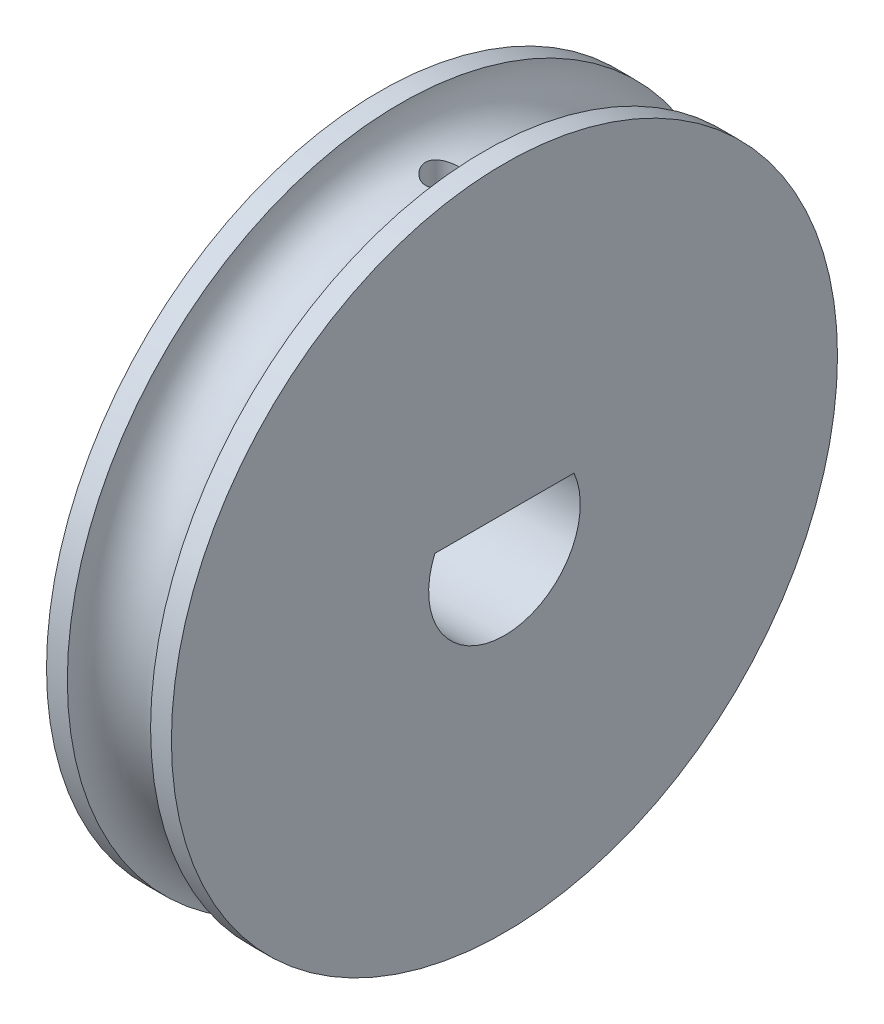
SolidWorks part; units mm, degrees
ref_plane "Front Plane" through (0, 0, 0) normal (0, 0, 1) x (1, 0, 0)
ref_plane "Top Plane" through (0, 0, 0) normal (0, 1, 0) x (1, 0, 0)
ref_plane "Right Plane" through (0, 0, 0) normal (1, 0, 0) x (0, 0, -1)
sketch "Sketch1" plane through (0, 0, 0) normal (1, 0, 0) x (0, 0, -1)
  line L0 (0, 0) -> (0, 9.1978)
  line L1 (-21.2164, 9.1978) -> (21.2164, 9.1978)
  circle A0 centre (0, 0) radius 101.6
  circle A1 centre (0, 0) radius 23.1244
  point P7 (0, 9.1978)
  point P8 (0, 0)
  dimension "D1" = 203.2
  dimension "D3" = 46.2487
  dimension "D2" = 9.1978
extrude "Boss-Extrude1" add sketch "Sketch1" against normal blind 38.1 contours A0 A1 | L1 A1
ref_plane "Plane1" through (0, 101.6, 0) normal (0, 1, 0) x (1, 0, 0)
sketch "Sketch2" plane through (0, 101.6, 0) normal (0, 1, 0) x (1, 0, 0)
  line L0 (-19.05, 101.6) -> (-19.05, -101.6) construction
  line L1 (0, 101.6) -> (-38.1, 101.6) construction
  line L2 (-38.1, -101.6) -> (0, -101.6) construction
  circle A0 centre (-19.05, 0) radius 5
  dimension "D1" = 10
extrude "Cut-Extrude1" cut sketch "Sketch2" against normal blind 63.5 contours L0 A0 | A0 L0
sketch "Sketch3" plane through (0, 38.1, 0) normal (0, 1, 0) x (1, 0, 0)
  circle A0 centre (-19.05, 0) radius 5 construction
  circle A1 centre (-19.05, 0) radius 5
  circle A2 centre (-19.05, 0) radius 1.5
  dimension "D1" = 3
extrude "Cut-Extrude4" cut sketch "Sketch3" against normal up to surface (28.9022 mm away) contours A2 up to face at (-19.05, 9.1978, 0)
sketch "Sketch4" plane through (0, 0, 0) normal (0, 1, 0) x (1, 0, 0)
  line L0 (-19.05, 0) -> (-19.05, -101.6) construction
  line L1 (-38.1, -101.6) -> (0, -101.6) construction
  line L3 (-38.1, 101.6) -> (-38.1, -101.6) construction
  line L4 (-18.3876, 0) -> (49981.6124, 0) construction
  circle A0 centre (-19.05, -101.6) radius 12.7
  point P8 (-31.75, -101.6)
  dimension "D1" = 6.35
revolve "Cut-Revolve1" cut sketch "Sketch4" angle 360 about L4
